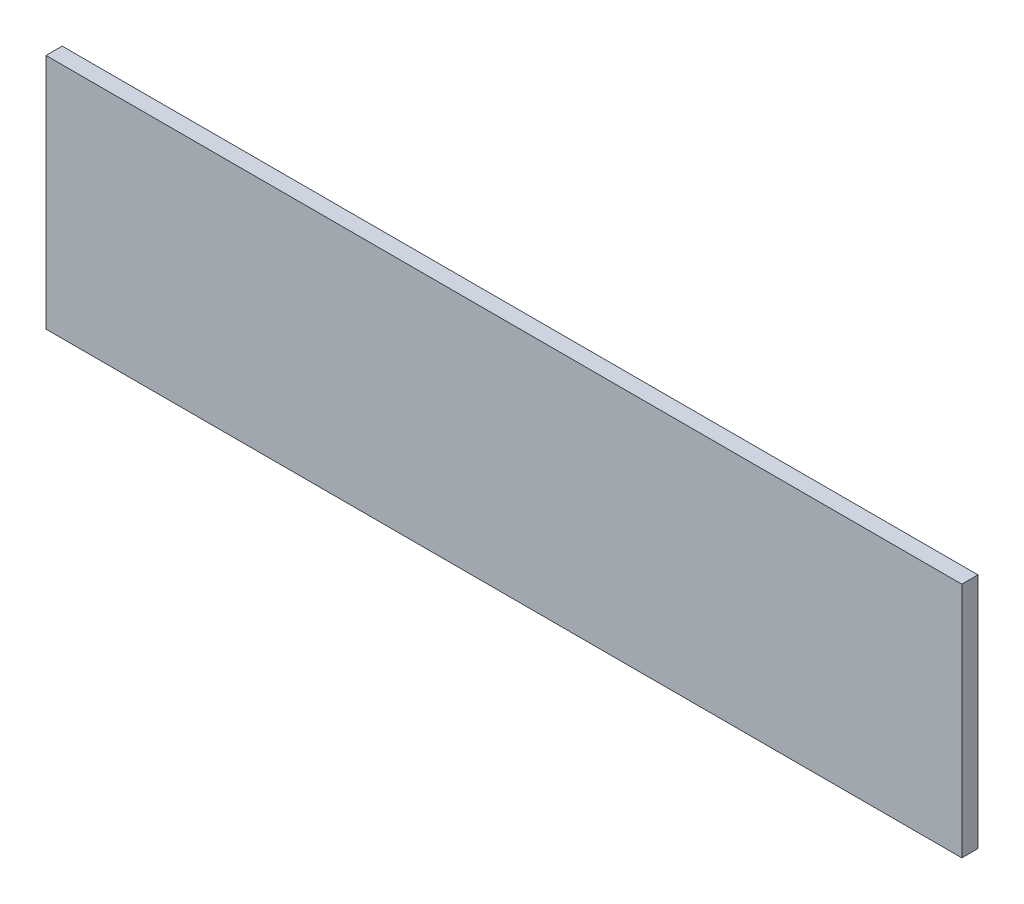
SolidWorks part; units mm, degrees
ref_plane "前视基准面" through (0, 0, 0) normal (0, 0, 1) x (1, 0, 0)
ref_plane "上视基准面" through (0, 0, 0) normal (0, 1, 0) x (1, 0, 0)
ref_plane "右视基准面" through (0, 0, 0) normal (1, 0, 0) x (0, 0, -1)
sketch "草图1" plane through (0, 0, 0) normal (0, 0, 1) x (1, 0, 0)
  line L1 (0, 0) -> (170, 0)
  line L2 (0, 0) -> (0, -44)
  line L3 (0, -44) -> (170, -44)
  line L4 (170, 0) -> (170, -44)
  dimension "D1" = 170
  dimension "D2" = 44
extrude "凸台-拉伸1" add sketch "草图1" along normal blind 3
